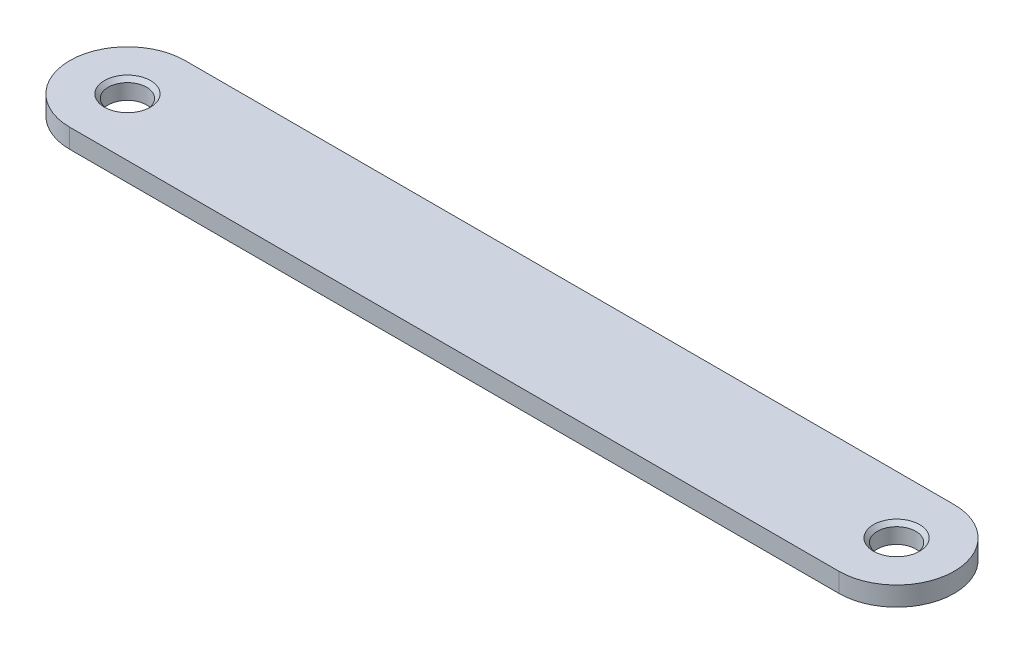
SolidWorks part; units mm, degrees
ref_plane "Front Plane" through (0, 0, 0) normal (0, 0, 1) x (1, 0, 0)
ref_plane "Top Plane" through (0, 0, 0) normal (0, 1, 0) x (1, 0, 0)
ref_plane "Right Plane" through (0, 0, 0) normal (1, 0, 0) x (0, 0, -1)
sketch "Sketch1" plane through (0, 0, 0) normal (0, 1, 0) x (1, 0, 0)
  line L0 (0, 0) -> (200, 0) construction
  line L1 (0, 15) -> (200, 15)
  line L2 (0, -15) -> (200, -15)
  arc A0 (0, 15) -> (0, -15) centre (0, 0) ccw
  arc A1 (200, -15) -> (200, 15) centre (200, 0) ccw
  circle A2 centre (0, 0) radius 5
  circle A3 centre (200, 0) radius 5
  point P3 (100, 0)
  dimension "D2" = 15
  dimension "D3" = 10
  dimension "D4" = 10
  dimension "D1" = 200
extrude "Boss-Extrude1" add sketch "Sketch1" along normal blind 5
chamfer "Chamfer1" distance 1 angle 45 1 edges at (200, 5, 5)
chamfer "Chamfer2" distance 1 angle 45 1 edges at (0, 5, 5)
